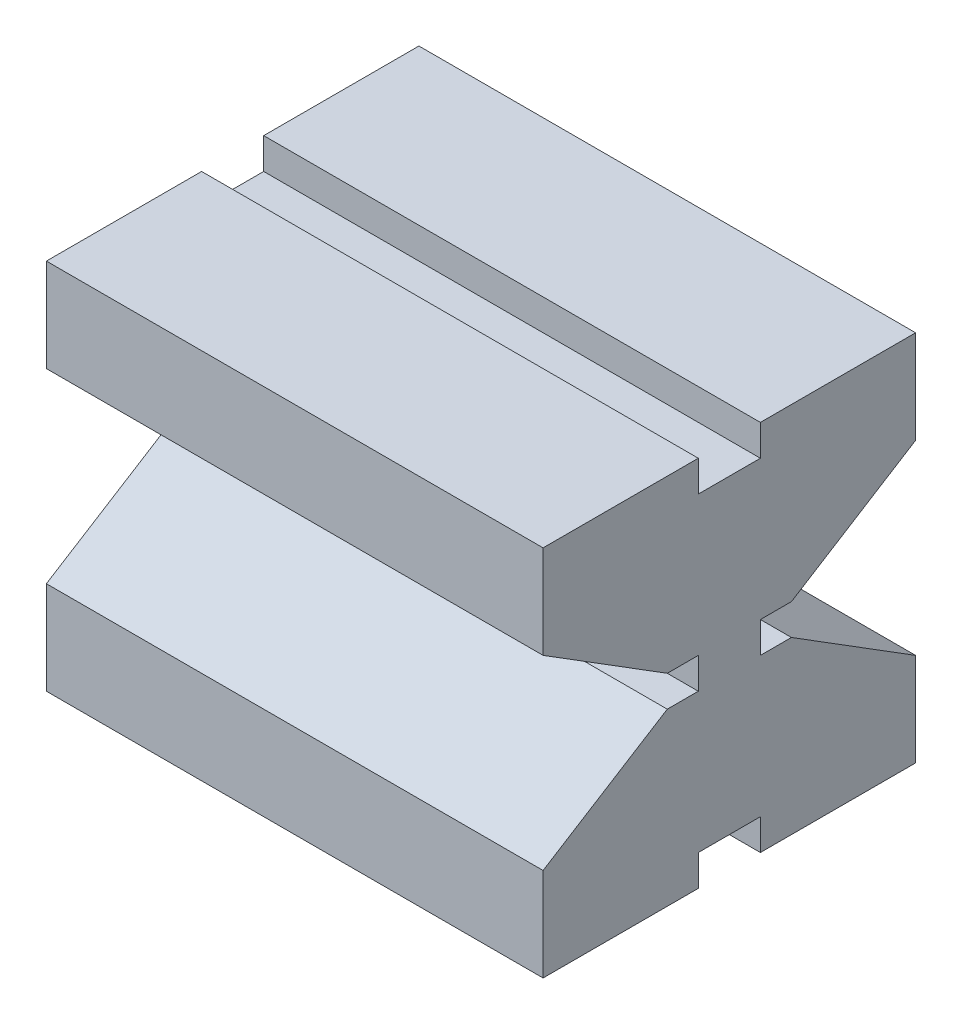
SolidWorks part; units mm, degrees
ref_plane "Front Plane" through (0, 0, 0) normal (1, 0, 0) x (0, 1, 0)
ref_plane "Top Plane" through (0, 0, 0) normal (0, 0, 1) x (0, 1, 0)
ref_plane "Right Plane" through (0, 0, 0) normal (0, 1, 0) x (-1, 0, 0)
sketch "Sketch1" plane through (0, 0, 0) normal (1, 0, 0) x (0, 1, 0)
  line L0 (-127.1399, 0) -> (123.7382, 0) construction
  line L1 (0, 107.7925) -> (0, -102.6899) construction
  line L2 (-30, 30) -> (-15, 30)
  line L3 (-15, 30) -> (-2.5, 10)
  line L4 (-2.5, 10) -> (-2.5, 5)
  line L5 (-2.5, 5) -> (2.5, 5)
  line L6 (-30, 30) -> (-30, 5)
  line L7 (-30, 5) -> (-25, 5)
  line L8 (-25, 5) -> (-25, -5)
  line L9 (-2.5, -5) -> (2.5, -5)
  line L10 (-30, -5) -> (-25, -5)
  line L11 (-30, -30) -> (-30, -5)
  line L12 (-2.5, -10) -> (-2.5, -5)
  line L13 (-15, -30) -> (-2.5, -10)
  line L14 (-30, -30) -> (-15, -30)
  line L15 (30, -30) -> (15, -30)
  line L16 (15, -30) -> (2.5, -10)
  line L17 (2.5, -10) -> (2.5, -5)
  line L18 (30, -30) -> (30, -5)
  line L19 (30, -5) -> (25, -5)
  line L20 (25, 5) -> (25, -5)
  line L21 (30, 5) -> (25, 5)
  line L22 (30, 30) -> (30, 5)
  line L23 (2.5, 10) -> (2.5, 5)
  line L24 (15, 30) -> (2.5, 10)
  line L25 (30, 30) -> (15, 30)
  point P14 (-25, 0)
  point P21 (0, 5)
  point P22 (0, -5)
  point P32 (25, 0)
  point P35 (-3.4446, -30.6807)
  dimension "D1" = 60
  dimension "D2" = 15
  dimension "D3" = 30
  dimension "D4" = 5
  dimension "D5" = 10
  dimension "D6" = 5
  dimension "D7" = 5
extrude "Boss-Extrude1" add sketch "Sketch1" against normal mid plane 80
